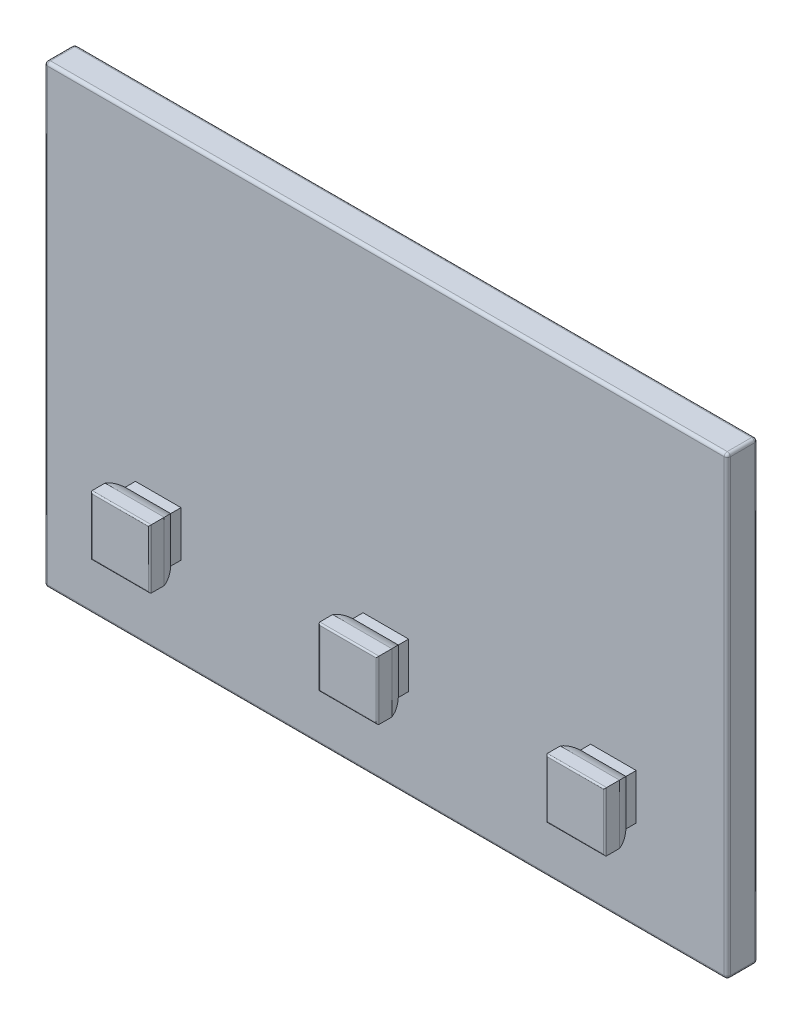
SolidWorks part; units mm, degrees
ref_plane "前视基准面" through (0, 0, 0) normal (0, 0, 1) x (1, 0, 0)
ref_plane "上视基准面" through (0, 0, 0) normal (0, 1, 0) x (1, 0, 0)
ref_plane "右视基准面" through (0, 0, 0) normal (1, 0, 0) x (0, 0, -1)
sketch "草图1" plane through (0, 0, 0) normal (0, 0, 1) x (1, 0, 0)
  line L1 (-22.5, -7.5) -> (22.5, -7.5)
  line L2 (-22.5, -7.5) -> (-22.5, 22.5)
  line L3 (-22.5, 22.5) -> (22.5, 22.5)
  line L4 (22.5, -7.5) -> (22.5, 22.5)
extrude "凸台-拉伸1" add sketch "草图1" against normal blind 2
sketch "草图2" plane through (0, 0, 0) normal (0, 0, 1) x (1, 0, 0)
  line L1 (-1.5, -1.5) -> (1.5, -1.5)
  line L2 (-1.5, -1.5) -> (-1.5, 1.5)
  line L3 (-1.5, 1.5) -> (1.5, 1.5)
  line L4 (1.5, -1.5) -> (1.5, 1.5)
extrude "凸台-拉伸2" add sketch "草图2" along normal blind 1
sketch "草图3" plane through (0, -1.5, 0) normal (0, -1, 0) x (1, 0, 0)
  line L0 (-1.95, 2.5) -> (1.95, 2.5)
  line L1 (-1.95, 2.5) -> (-1.95, 1.5556)
  line L2 (1.95, 2.5) -> (1.95, 1.5556)
  line L4 (-1.5, 0.6771) -> (1.5, 0.6771)
  arc A1 (-1.95, 1.5556) -> (-1.5, 0.6771) centre (0, 2) ccw
  arc A2 (1.5, 0.6771) -> (1.95, 1.5556) centre (0, 2) ccw
extrude "凸台-拉伸3" add sketch "草图3" along normal blind 1 and the other way blind 4
sketch "草图4" plane through (-1.95, 0, 0) normal (-1, 0, 0) x (0, 0, 1)
  line L0 (0.6771, 1.5) -> (0.6771, 2.5)
  line L1 (0.6771, -2.5) -> (2.5, -2.5)
  line L2 (0.6771, -2.5) -> (0.6771, -1.5)
  line L3 (0.6771, 2.5) -> (2.5, 2.5)
  line L4 (2.5, -2.5) -> (2.5, -1.95)
  line L5 (1.5556, -1.95) -> (2.5, -1.95)
  line L6 (2.5, 1.95) -> (2.5, 2.5)
  line L7 (1.5556, 1.95) -> (2.5, 1.95)
  arc A1 (1.5556, 1.95) -> (0.6771, 1.5) centre (2, 0) ccw
  arc A2 (0.6771, -1.5) -> (1.5556, -1.95) centre (2, 0) ccw
extrude "切除-拉伸1" cut sketch "草图4" against normal up to next
ref_plane "基准面1" through (7.5, 0, 0) normal (1, 0, 0) x (0, 0, -1)
ref_plane "基准面2" through (-7.5, 0, 0) normal (1, 0, 0) x (0, 0, -1)
mirror "镜向1" about plane through (7.5, 0, 0) normal (1, 0, 0) of "凸台-拉伸2", "凸台-拉伸3", "切除-拉伸1"
mirror "镜向2" about plane through (-7.5, 0, 0) normal (1, 0, 0) of "凸台-拉伸2", "凸台-拉伸3", "切除-拉伸1"
fillet "圆角1" radius 0.1 12 edges at (16.95, 0, 2.5) (15, -1.95, 2.5) (13.05, 0, 2.5) (15, 1.95, 2.5) (1.95, 0, 2.5) (0, -1.95, 2.5) (-1.95, 0, 2.5) (0, 1.95, 2.5) (-13.05, 0, 2.5) (-15, -1.95, 2.5) (-16.95, 0, 2.5) (-15, 1.95, 2.5)
fillet "圆角2" radius 0.2 12 edges at (0, -7.5, -2) (0, -7.5, 0) (-22.5, -7.5, -1) (-22.5, 7.5, -2) (-22.5, 7.5, 0) (22.5, 7.5, -2) (22.5, -7.5, -1) (22.5, 7.5, 0) (-22.5, 22.5, -1) (0, 22.5, -2) (22.5, 22.5, -1) (0, 22.5, 0)
